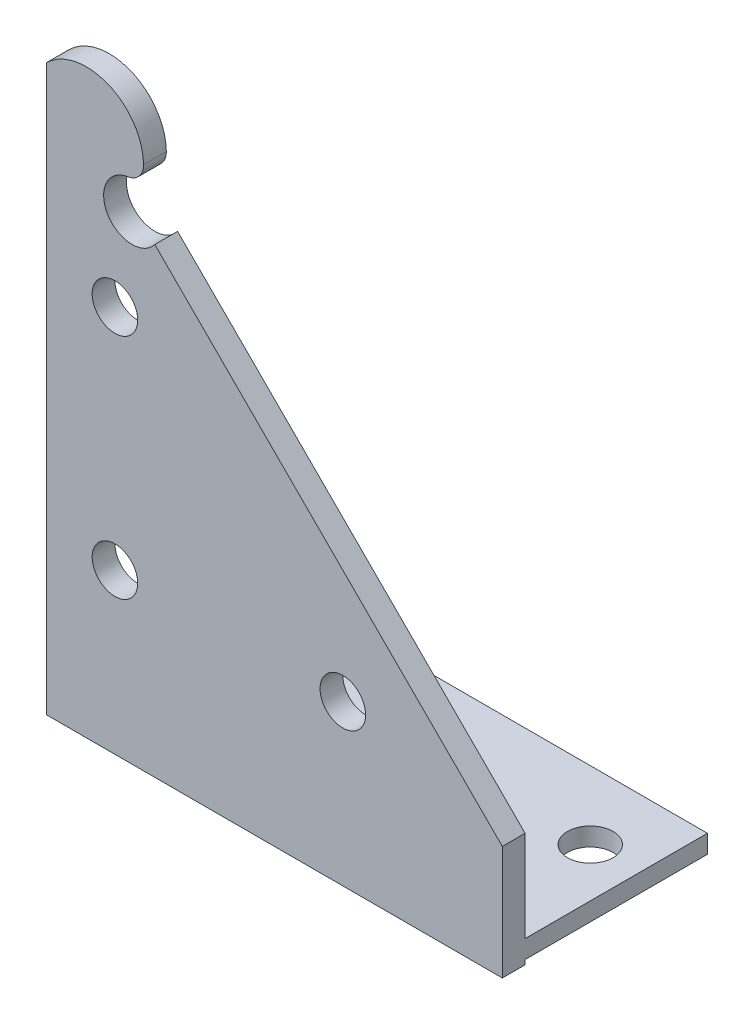
SolidWorks part; units mm, degrees
ref_plane "Front Plane" through (0, 0, 0) normal (0, 0, 1) x (1, 0, 0)
ref_plane "Top Plane" through (0, 0, 0) normal (0, 1, 0) x (1, 0, 0)
ref_plane "Right Plane" through (0, 0, 0) normal (1, 0, 0) x (0, 0, -1)
sketch "Sketch1" plane through (0, 0, 0) normal (0, 0, 1) x (1, 0, 0)
  line L0 (0, 0) -> (63.5, 0)
  line L1 (63.5, 0) -> (63.5, 15.875)
  line L2 (63.5, 15.875) -> (15.0803, 64.2947)
  line L3 (0, 78.7051) -> (0, 0)
  circle A0 centre (9.525, 22.225) radius 3.175
  circle A1 centre (9.525, 53.975) radius 3.175
  circle A2 centre (41.275, 22.225) radius 3.175
  arc A3 (0, 78.7051) -> (13.5118, 73.1485) centre (5.5626, 73.025) cw
  arc A4 (11.3395, 70.5957) -> (15.0803, 64.2947) centre (11.9126, 66.675) ccw
  arc A5 (13.5118, 73.1485) -> (11.3395, 70.5957) centre (10.9721, 73.109) cw
  point P16 (0, 0)
  point P18 (47.4405, 22.225)
  dimension "D2" = 6.35
  dimension "D3" = 6.35
  dimension "D4" = 6.35
  dimension "D11" = 7.9502
  dimension "D12" = 3.9624
  dimension "D14" = 2.54
  dimension "D1" = 63.5
  dimension "D5" = 22.225
  dimension "D6" = 31.75
  dimension "D7" = 15.875
  dimension "D8" = 31.75
  dimension "D9" = 6.35
  dimension "D10" = 6.35
  dimension "D13" = 19.05
  dimension "D15" = 45
  dimension "D16" = 9.525
  dimension "D17" = 5.5626
extrude "Boss-Extrude1" add sketch "Sketch1" along normal blind 3.175
sketch "Sketch2" plane through (0, 0, 0) normal (0, 0, -1) x (-1, 0, 0)
  line L0 (-63.5, 3.175) -> (0, 3.175)
  line L1 (-63.5, 0) -> (-63.5, 15.875) construction
  line L2 (0, 78.7051) -> (0, 0) construction
  line L3 (0, 0) -> (-63.5, 0) construction
  dimension "D1" = 3.175
extrude "Extrude-Thin1" add sketch "Sketch2" along normal blind 25.4 thin
sketch "Sketch3" plane through (0, 3.175, 0) normal (0, 1, 0) x (1, 0, 0)
  line L0 (31.75, 25.4) -> (31.75, 50025.4) construction
  line L1 (63.5, 25.4) -> (0, 25.4) construction
  line L2 (0, 25.4) -> (0, 0) construction
  circle A0 centre (31.75, 12.7) radius 3.175
  circle A1 centre (9.525, 15.875) radius 3.175
  circle A2 centre (56.6994, 15.875) radius 3.175
  point P6 (0, 0)
  point P11 (31.75, 25.4)
  dimension "D1" = 6.35
  dimension "D2" = 9.525
  dimension "D3" = 9.525
  dimension "D4" = 3.175
extrude "Cut-Extrude1" cut sketch "Sketch3" against normal blind 25.4
